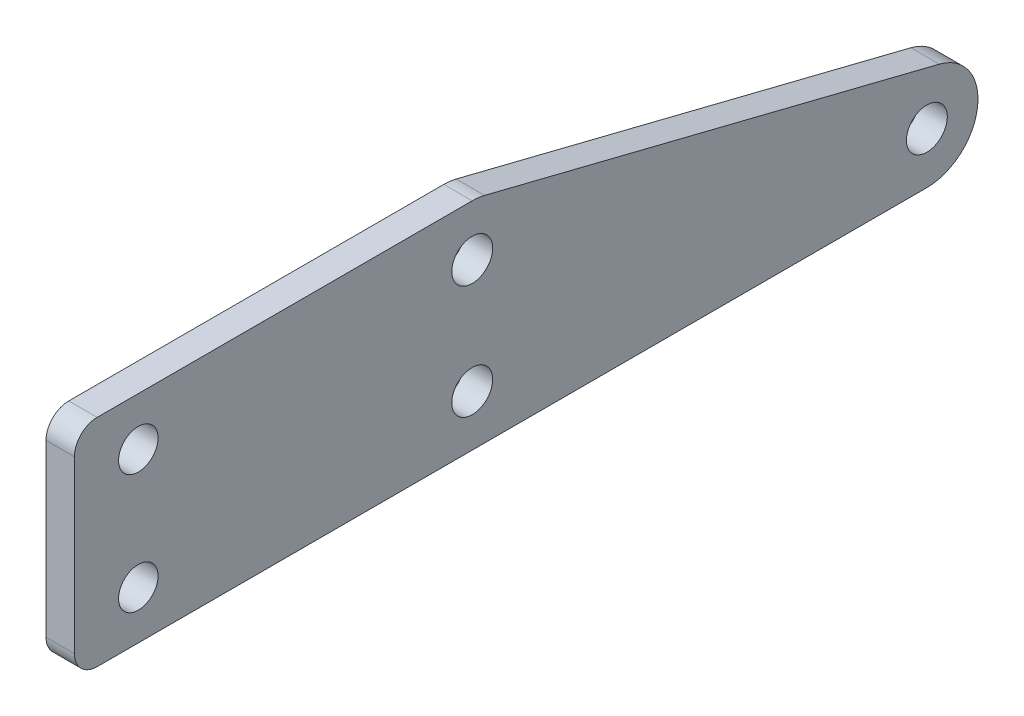
SolidWorks part; units mm, degrees
material "Acrylic (Medium-high impact)"
ref_plane "Front Plane" through (0, 0, 0) normal (0, 0, 1) x (1, 0, 0)
ref_plane "Top Plane" through (0, 0, 0) normal (0, 1, 0) x (1, 0, 0)
ref_plane "Right Plane" through (0, 0, 0) normal (1, 0, 0) x (0, 0, -1)
sketch "Sketch1" plane through (0, 0, 0) normal (1, 0, 0) x (0, 0, -1)
  line L0 (0, 6.35) -> (0, -6.35) construction
  line L1 (0, -6.35) -> (50.8, -6.35) construction
  line L2 (50.8, -6.35) -> (0, 6.35) construction
  line L3 (0, 6.35) -> (50.8, 6.35) construction
  line L4 (50.8, 6.35) -> (50.8, -6.35) construction
  line L5 (1.3861, 11.8944) -> (52.1861, -0.8056)
  line L6 (0, -12.065) -> (50.8, -12.065)
  line L7 (0, 12.065) -> (-41.91, 12.065)
  line L8 (-44.45, 9.525) -> (-44.45, -9.525)
  line L9 (-41.91, -12.065) -> (0, -12.065)
  circle A0 centre (0, 6.35) radius 2.286
  circle A1 centre (0, -6.35) radius 2.286
  circle A2 centre (50.8, -6.35) radius 2.286
  circle A3 centre (0, -6.35) radius 5.715 construction
  circle A4 centre (0, 6.35) radius 5.715 construction
  circle A5 centre (50.8, -6.35) radius 5.715 construction
  circle A6 centre (50.8, 6.35) radius 2.286 construction
  circle A7 centre (50.8, 6.35) radius 5.715 construction
  arc A8 (50.8, -12.065) -> (52.1861, -0.8056) centre (50.8, -6.35) ccw
  arc A9 (1.3861, 11.8944) -> (0, 12.065) centre (0, 6.35) ccw
  arc A10 (-44.45, -9.525) -> (-41.91, -12.065) centre (-41.91, -9.525) ccw
  arc A11 (-41.91, 12.065) -> (-44.45, 9.525) centre (-41.91, 9.525) ccw
  dimension "D1" = 4.572
  dimension "D4" = 11.43
  dimension "D5" = 2.54
  dimension "D2" = 12.7
  dimension "D3" = 50.8
  dimension "D6" = 44.45
extrude "Boss-Extrude1" add sketch "Sketch1" along normal blind 3.175
sketch "Sketch2" plane through (3.175, 0, 0) normal (1, 0, 0) x (0, 0, -1)
  line L0 (-39.5202, 11.1655) -> (-39.5202, -7.8845) construction
  line L1 (-35.1004, -7.8845) -> (-35.1004, 11.1655) construction
  line L2 (-37.3103, 6.6801) -> (-37.3103, -6.6801) construction
  line L3 (-37.3103, 8.89) -> (-37.3103, 12.065) construction
  line L4 (0, 12.065) -> (-41.91, 12.065) construction
  line L5 (-37.3103, -8.89) -> (-37.3103, -12.065) construction
  line L6 (-41.91, -12.065) -> (50.8, -12.065) construction
  circle A0 centre (-37.3103, 6.6801) radius 2.2099
  circle A1 centre (-37.3103, -6.6801) radius 2.2099
  dimension "D1" = 3.175
extrude "Cut-Extrude1" cut sketch "Sketch2" against normal through all
